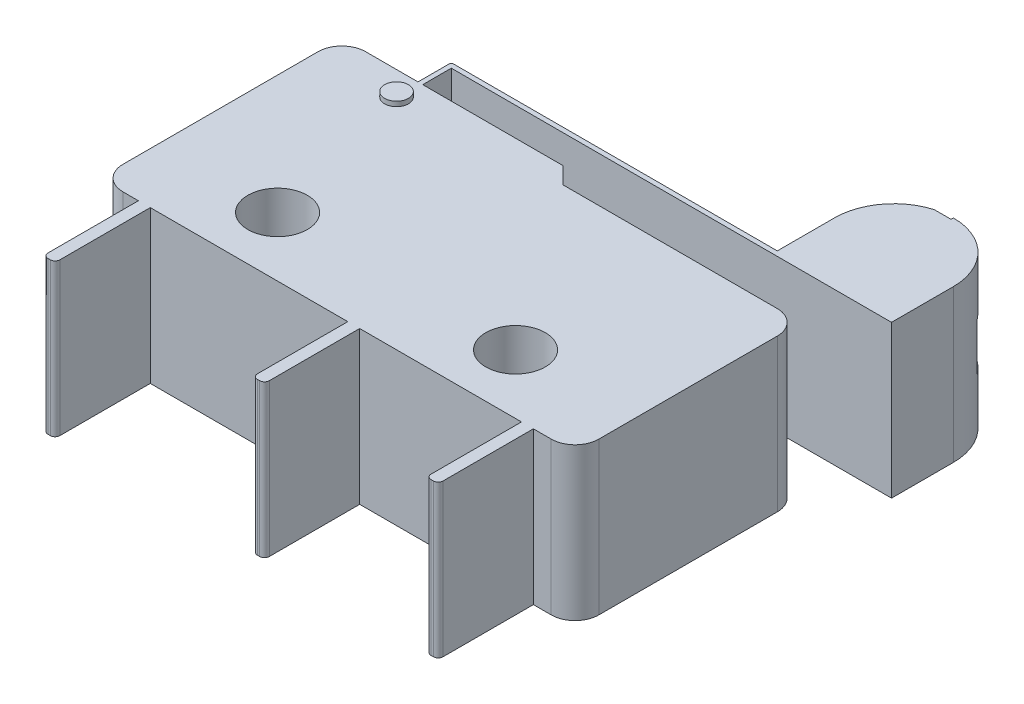
SolidWorks part; units mm, degrees
ref_plane "Front Plane" through (0, 0, 0) normal (0, 0, 1) x (1, 0, 0)
ref_plane "Top Plane" through (0, 0, 0) normal (0, 1, 0) x (1, 0, 0)
ref_plane "Right Plane" through (0, 0, 0) normal (1, 0, 0) x (0, 0, -1)
sketch "Sketch1" plane through (0, 0, 0) normal (0, 1, 0) x (1, 0, 0)
  line L0 (0, 0) -> (20, 0)
  line L1 (0, 0) -> (0, 10.2)
  line L2 (20, 0) -> (20, 9.5)
  line L3 (0, 10.2) -> (9.3, 10.2)
  line L4 (20, 9.5) -> (10, 9.5)
  line L5 (10, 9.5) -> (9.3, 10.2)
  dimension "D1" = 20
  dimension "D2" = 10.2
  dimension "D3" = 9.5
  dimension "D5" = 10
  dimension "D6" = 45
extrude "Boss-Extrude1" add sketch "Sketch1" along normal blind 6.4
fillet "Fillet1" radius 1 4 edges at (0, 3.2, 0) (20, 3.2, 0) (20, 3.2, -9.5) (0, 3.2, -10.2)
sketch "Sketch2" plane through (0, 6.4, 0) normal (0, 1, 0) x (1, 0, 0)
  line L0 (0, 9.2) -> (3.3, 9.2)
  circle A0 centre (3.3, 9.2) radius 0.5
  dimension "D2" = 1
  dimension "D1" = 3.3
extrude "Boss-Extrude2" add sketch "Sketch2" along normal blind 0.2
sketch "Sketch3" plane through (0, 6.4, 0) normal (0, 1, 0) x (1, 0, 0)
  line L0 (3.3, 9.2) -> (3.3, 11.5)
  line L1 (3.3, 0) -> (3.3, 11.5)
  line L2 (1, 0) -> (19, 0) construction
  line L3 (3.3, 11.5) -> (21.9, 11.5)
  line L4 (3.4, 9.2) -> (3.4, 11.5)
  line L5 (3.3, 11.4) -> (21.9, 11.4)
  line L6 (3.2, 9.2) -> (3.2, 11.5)
  line L7 (3.3, 11.6) -> (21.9, 11.6)
  line L8 (3.2, 9.2) -> (3.3874, 9.2)
  line L9 (21.9, 11.6) -> (21.9, 11.4)
  circle A0 centre (3.3, 11.5) radius 0.1
  line M13 (9.3, 10.2) -> (1, 10.2)
  dimension "D1" = 18.6
  dimension "D2" = 11.5
  dimension "D3" = 0.1
  dimension "D4" = 0.1
extrude "Boss-Extrude3" add sketch "Sketch3" against normal up to surface (6.4 mm away) contours A0 L3 L9 L7 | L9 L3 L4 L5 | A0 L5 L4 | L1 A0 L3 | L3 A0 L1 | L5 L0 L4 M13 | A0 L6 L0 M13 up to face at (9.93, 0, -5.91)
sketch "Sketch4" plane through (0, 6.4, 0) normal (0, 1, 0) x (1, 0, 0)
  line L0 (21.9, 11.5) -> (16.9, 11.5)
  line L1 (21.9, 11.6) -> (21.9, 11.4) construction
  line L2 (19.4, 11.5) -> (19.4, 16.5)
  line L3 (16.9, 11.5) -> (16.9, 14)
  line L4 (21.9, 11.5) -> (21.9, 14)
  circle A0 centre (19.4, 14) radius 2.5
  line M17 (21.9, 11.6) -> (3.3, 11.6)
  dimension "D1" = 5
  dimension "D2" = 5
extrude "Boss-Extrude4" add sketch "Sketch4" against normal up to surface (6.4 mm away) contours A0 L4 M17 | A0 L2 M17 | L2 A0 M17 | A0 L3 M17 up to face at (9.387, 0, -8.06)
sketch "Sketch5" plane through (0, 6.4, 0) normal (0, 1, 0) x (1, 0, 0)
  line L0 (0, 0) -> (0, 2.5)
  line L1 (0, 9.2) -> (0, 1) construction
  line L2 (0, 2.5) -> (10, 2.5)
  line L3 (10, 2.5) -> (10, 0)
  circle A0 centre (5, 2.5) radius 1.25
  circle A1 centre (15, 2.5) radius 1.25
  dimension "D2" = 2.5
  dimension "D1" = 2.5
extrude "Cut-Extrude1" cut sketch "Sketch5" against normal through all contours A1 | L2 A0 | L2 A0
sketch "Sketch6" plane through (0, 6.4, 0) normal (0, 1, 0) x (1, 0, 0)
  line L0 (0, 0) -> (0, -4)
  line L1 (2.15, -4) -> (2.15, 0)
  line L2 (1.65, -4) -> (1.65, 0)
  line L3 (1, 0) -> (19, 0) construction
  line L4 (1.65, -4) -> (2.15, -4)
  line L5 (1.65, 0) -> (2.15, 0)
  line L6 (1.65, -4) -> (6.05, -4)
  line L7 (10.95, -4) -> (10.95, 0)
  line L8 (6.05, -4) -> (6.05, -2.8834)
  line L9 (10.45, -4) -> (10.45, 0)
  line L10 (17.75, -4) -> (17.75, 0)
  line L11 (18.25, -4) -> (18.25, 0)
  line L12 (10.45, 0) -> (10.95, 0)
  line L13 (17.75, 0) -> (18.25, 0)
  line L14 (18.25, -4) -> (17.75, -4)
  line L15 (10.95, -4) -> (10.45, -4)
  line M5 (1, 0) -> (19, 0)
  dimension "D1" = 4
  dimension "D2" = 1.65
  dimension "D4" = 8.8
  dimension "D5" = 7.3
  dimension "D3" = 0.5
  dimension "D6" = 0.5
extrude "Boss-Extrude5" add sketch "Sketch6" against normal up to surface (6.4 mm away) contours L2 L4 L1 M5 | L15 L7 L9 M5 | L14 L11 L10 M5 up to face at (10.1779, 0, -8.8169)
fillet "Fillet2" radius 0.2 6 edges at (18.25, 3.2, 4) (17.75, 3.2, 4) (10.95, 3.2, 4) (10.45, 3.2, 4) (2.15, 3.2, 4) (1.65, 3.2, 4)
sketch "Sketch7" plane through (0, 6.4, 0) normal (0, 1, 0) x (1, 0, 0)
  line L0 (19.4, 16.5) -> (19.4, 16.4)
  line L1 (19.4, 16.4) -> (18.1026, 16.4)
  line L2 (18.1026, 16.4) -> (20.4175, 16.4)
  line L3 (20.4175, 16.4) -> (20.4175, 16.5945)
  line L4 (20.4175, 16.5945) -> (18.1026, 16.5945)
  line L5 (18.1026, 16.5945) -> (18.1026, 16.4)
  arc A0 (21.9, 14) -> (16.9, 14) centre (19.4, 14) ccw construction
  arc M21 (21.9, 14) -> (16.9, 14) centre (19.4, 14) ccw
  dimension "D1" = 0.1
extrude "Cut-Extrude2" cut sketch "Sketch7" against normal blind 10 contours L4 L5 L1 L2 L3 M21 | L1 L0 M21
sketch "Sketch9" plane through (16.9, 0, 0) normal (-1, 0, 0) x (0, 0, 1)
  line L0 (-16.5, 3.2) -> (-15.5, 3.2)
  line L1 (-16.5, 0) -> (-16.5, 6.4) construction
  line L3 (-16.5, 2.2) -> (-15.5, 2.2)
  line L4 (-16.5, 4.2) -> (-15.5, 4.2)
  line L5 (-15.5, 2.2) -> (-15.5, 4.2)
  line L6 (-16.5, 2.2) -> (-16.5, 4.2)
  dimension "D1" = 1
  dimension "D2" = 1
  dimension "D3" = 1
extrude "Cut-Extrude3" cut sketch "Sketch9" against normal through all both and the other way through all contours L6 L0 L5 L4 | L6 L3 L5 L0
